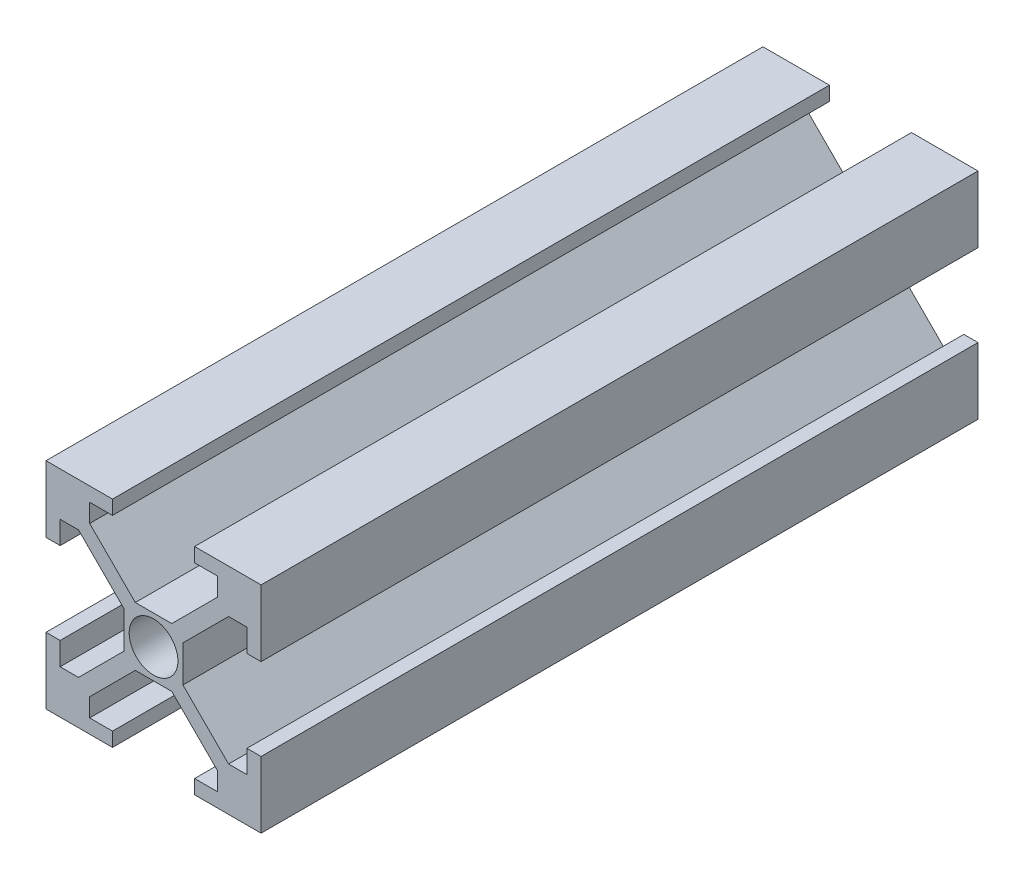
SolidWorks part; units mm, degrees
ref_plane "Front Plane" through (0, 0, 0) normal (0, 0, 1) x (1, 0, 0)
ref_plane "Top Plane" through (0, 0, 0) normal (0, 1, 0) x (1, 0, 0)
ref_plane "Right Plane" through (0, 0, 0) normal (1, 0, 0) x (0, 0, -1)
sketch "Sketch3" plane through (0, 0, 0) normal (0, 0, 1) x (1, 0, 0)
  line L0 (0, 0) -> (0.7778, -0.7778)
  line L5 (-4.1, 4.1) -> (4.1, -4.1) construction
  line L6 (-4.1, -4.1) -> (4.1, 4.1) construction
  line L7 (0, 0) -> (-0.7778, 0.7778)
  line L8 (-0.7778, 0.7778) -> (-4.1, -2.5444) construction
  line L9 (0.7778, -0.7778) -> (-2.5444, -4.1) construction
  line L10 (-4.1, -2.5444) -> (-10.464, -8.9083)
  line L11 (-15, -15) -> (15, -15)
  line L12 (-15, -15) -> (-15, 15)
  line L13 (-15, 15) -> (15, 15)
  line L14 (15, -15) -> (15, 15)
  line L15 (-15, -15) -> (15, 15) construction
  line L16 (-15, 15) -> (15, -15) construction
  line L17 (-15, 0) -> (15, 0) construction
  line L18 (0, -15) -> (0, 15) construction
  line L19 (-2.5444, -4.1) -> (-8.9083, -10.464)
  line L20 (-8.9083, -10.464) -> (-8.9083, -13.0281)
  line L21 (-8.9083, -13.0281) -> (-5.7263, -13.0281)
  line L22 (-5.7263, -13.0281) -> (-5.7263, -15)
  line L23 (-13.0281, -5.7263) -> (-15, -5.7263)
  line L24 (-13.0281, -8.9083) -> (-13.0281, -5.7263)
  line L25 (-10.464, -8.9083) -> (-13.0281, -8.9083)
  line L26 (-5.7263, 13.0281) -> (-5.7263, 15)
  line L27 (-8.9083, 13.0281) -> (-5.7263, 13.0281)
  line L28 (-8.9083, 10.464) -> (-8.9083, 13.0281)
  line L29 (-2.5444, 4.1) -> (-8.9083, 10.464)
  line L30 (-4.1, 2.5444) -> (-10.464, 8.9083)
  line L31 (-10.464, 8.9083) -> (-13.0281, 8.9083)
  line L32 (-13.0281, 8.9083) -> (-13.0281, 5.7263)
  line L33 (-13.0281, 5.7263) -> (-15, 5.7263)
  line L34 (5.7263, 13.0281) -> (5.7263, 15)
  line L35 (8.9083, 13.0281) -> (5.7263, 13.0281)
  line L36 (8.9083, 10.464) -> (8.9083, 13.0281)
  line L37 (2.5444, 4.1) -> (8.9083, 10.464)
  line L38 (4.1, 2.5444) -> (10.464, 8.9083)
  line L39 (10.464, 8.9083) -> (13.0281, 8.9083)
  line L40 (13.0281, 8.9083) -> (13.0281, 5.7263)
  line L41 (13.0281, 5.7263) -> (15, 5.7263)
  line L42 (5.7263, -13.0281) -> (5.7263, -15)
  line L43 (8.9083, -13.0281) -> (5.7263, -13.0281)
  line L44 (8.9083, -10.464) -> (8.9083, -13.0281)
  line L45 (2.5444, -4.1) -> (8.9083, -10.464)
  line L46 (13.0281, -5.7263) -> (15, -5.7263)
  line L47 (13.0281, -8.9083) -> (13.0281, -5.7263)
  line L48 (10.464, -8.9083) -> (13.0281, -8.9083)
  line L49 (4.1, -2.5444) -> (10.464, -8.9083)
  line L50 (-2.5444, -4.1) -> (2.5444, -4.1)
  line L51 (4.1, -2.5444) -> (4.1, 2.5444)
  line L52 (2.5444, 4.1) -> (-2.5444, 4.1)
  line L53 (-4.1, 2.5444) -> (-4.1, -2.5444)
  circle A0 centre (0, 0) radius 3.4
  dimension "D1" = 6.8
  dimension "D4" = 1.1
  dimension "D5" = 1.1
  dimension "D6" = 2.2
  dimension "D7" = 30
  dimension "D8" = 30
  dimension "D9" = 9
extrude "Boss-Extrude1" add sketch "Sketch3" along normal blind 100 contours L30 L53 L10 L25 L24 L23 L12 L11 L22 L21 L20 L19 L50 L45 L44 L43 L42 L14 L46 L47 L48 L49 L51 L38 L39 L40 L41 L13 L34 L35 L36 L37 L52 L29 L28 L27 L26 L33 L32 L31 A0
